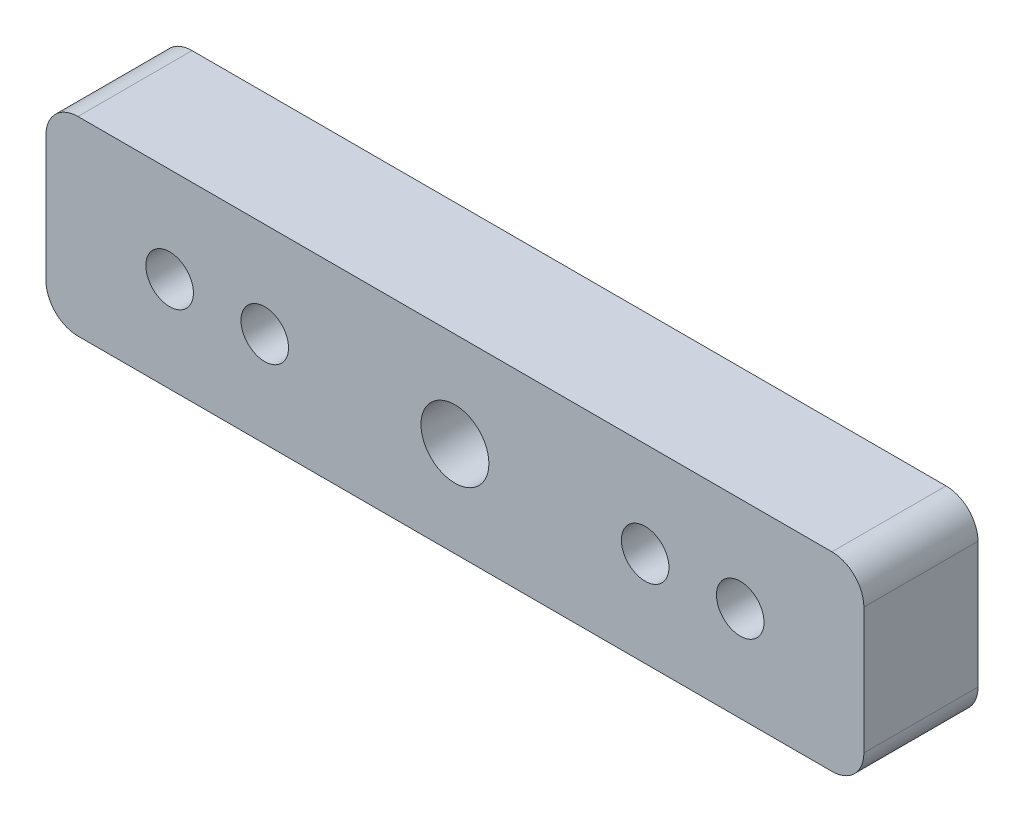
SolidWorks part; units mm, degrees
ref_plane "Front Plane" through (0, 0, 0) normal (0, 0, 1) x (1, 0, 0)
ref_plane "Top Plane" through (0, 0, 0) normal (0, 1, 0) x (1, 0, 0)
ref_plane "Right Plane" through (0, 0, 0) normal (1, 0, 0) x (0, 0, -1)
sketch "Sketch1" plane through (0, 0, 0) normal (0, 0, 1) x (1, 0, 0)
  line L0 (20, 0) -> (30, 0) construction
  line L1 (-39.64, -10) -> (39.64, -10)
  line L2 (-43, -6.64) -> (-43, 6.64)
  line L3 (-39.64, 10) -> (39.64, 10)
  line L4 (43, -6.64) -> (43, 6.64)
  line L5 (-43, -10) -> (43, 10) construction
  line L6 (-43, 10) -> (43, -10) construction
  line L7 (-20, 0) -> (20, 0) construction
  line L8 (-43, 0) -> (-30, 0) construction
  line L9 (-30, 0) -> (-20, 0) construction
  line L10 (-20, 0) -> (0, 0) construction
  line L11 (30, 0) -> (43, 0) construction
  circle A0 centre (-30, 0) radius 2.5
  circle A1 centre (0, 0) radius 3.57
  circle A2 centre (30, 0) radius 2.5
  circle A3 centre (-20, 0) radius 2.5
  circle A4 centre (20, 0) radius 2.5
  arc A5 (39.64, 10) -> (43, 6.64) centre (39.64, 6.64) cw
  arc A6 (39.64, -10) -> (43, -6.64) centre (39.64, -6.64) ccw
  arc A7 (-39.64, -10) -> (-43, -6.64) centre (-39.64, -6.64) cw
  arc A8 (-43, 6.64) -> (-39.64, 10) centre (-39.64, 6.64) cw
  point P0 (0, 0)
  dimension "D3" = 5
  dimension "D5" = 5
  dimension "D7" = 3.36
  dimension "D1" = 20
  dimension "D2" = 86
  dimension "D4" = 30
  dimension "D6" = 20
extrude "Boss-Extrude1" add sketch "Sketch1" along normal mid plane 12
